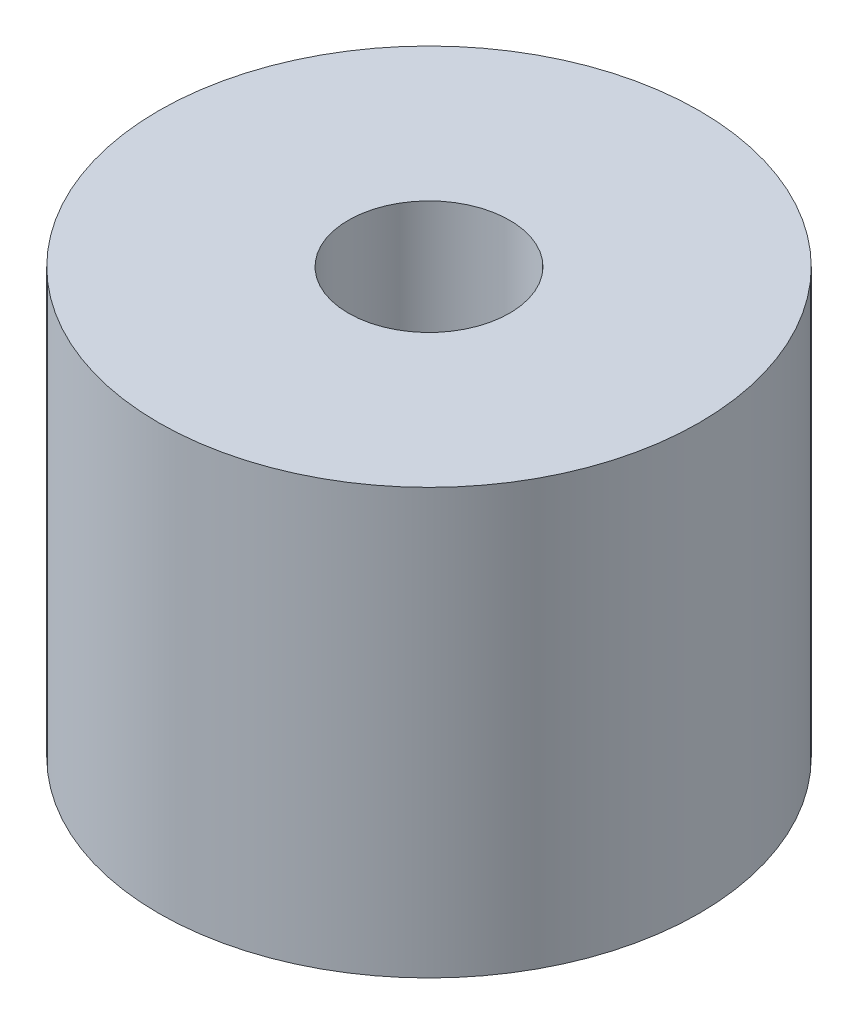
SolidWorks part; units mm, degrees
ref_plane "Front Plane" through (0, 0, 0) normal (0, 0, 1) x (1, 0, 0)
ref_plane "Top Plane" through (0, 0, 0) normal (0, 1, 0) x (1, 0, 0)
ref_plane "Right Plane" through (0, 0, 0) normal (1, 0, 0) x (0, 0, -1)
sketch "Sketch1" plane through (0, 0, 0) normal (0, 1, 0) x (1, 0, 0)
  circle A1 centre (0, 0) radius 14.25
  circle A2 centre (0, 0) radius 4.25
  dimension "D1" = 8.5
  dimension "D2" = 28.5
extrude "Boss-Extrude2" add sketch "Sketch1" along normal blind 22.4
